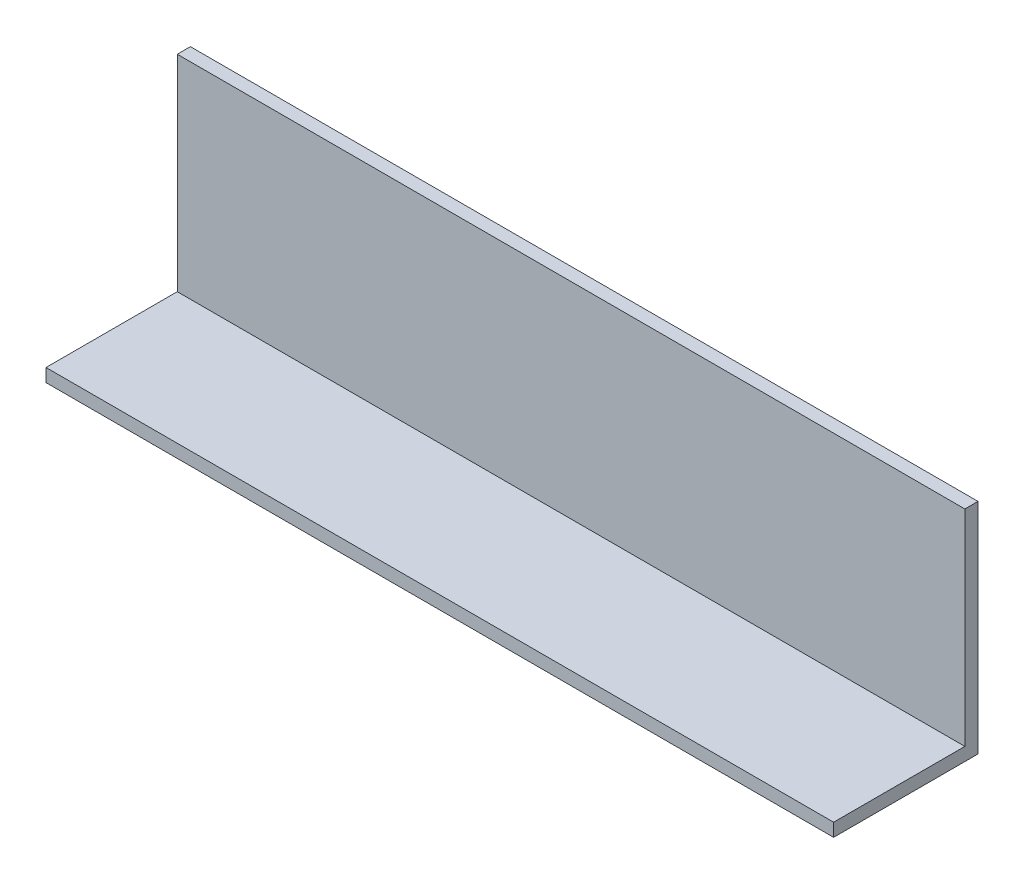
SolidWorks part; units mm, degrees
ref_plane "Front Plane" through (0, 0, 0) normal (0, 0, 1) x (1, 0, 0)
ref_plane "Top Plane" through (0, 0, 0) normal (0, 1, 0) x (1, 0, 0)
ref_plane "Right Plane" through (0, 0, 0) normal (1, 0, 0) x (0, 0, -1)
sketch "Sketch1" plane through (0, 0, 0) normal (0, 0, 1) x (1, 0, 0)
  line L1 (-900, 250) -> (900, 250)
  line L2 (-900, 250) -> (-900, -250)
  line L3 (-900, -250) -> (900, -250)
  line L4 (900, 250) -> (900, -250)
  line L5 (-900, 250) -> (900, -250) construction
  line L6 (-900, -250) -> (900, 250) construction
  point P0 (0, 0)
  dimension "D1" = 1800
  dimension "D2" = 500
extrude "Boss-Extrude1" add sketch "Sketch1" along normal blind 30
sketch "Sketch2" plane through (0, 0, 30) normal (0, 0, 1) x (1, 0, 0)
  line L0 (900, -250) -> (900, 250) construction
  line L1 (-900, -250) -> (900, -250)
  line L2 (-900, -250) -> (-900, -220)
  line L3 (-900, -220) -> (900, -220)
  line L4 (900, -250) -> (900, -220)
  dimension "D1" = 30
extrude "Boss-Extrude2" add sketch "Sketch2" along normal blind 300
